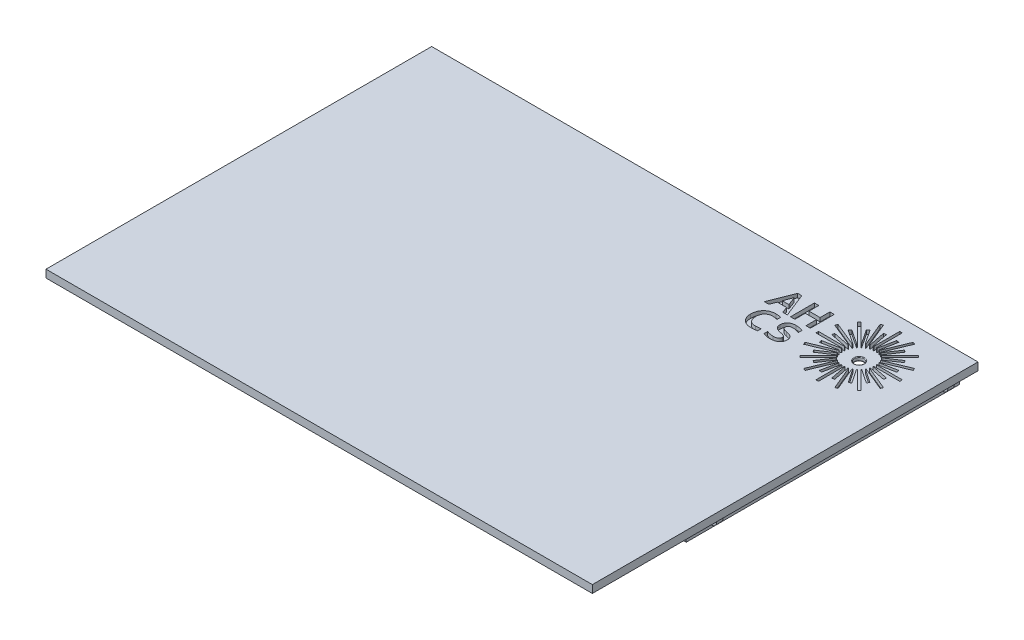
SolidWorks part; units mm, degrees
ref_plane "Front Plane" through (0, 0, 0) normal (0, 0, 1) x (1, 0, 0)
ref_plane "Top Plane" through (0, 0, 0) normal (0, 1, 0) x (1, 0, 0)
ref_plane "Right Plane" through (0, 0, 0) normal (1, 0, 0) x (0, 0, -1)
sketch "Sketch1" plane through (0, 0, 0) normal (0, 1, 0) x (1, 0, 0)
  line L1 (-107.95, -57.15) -> (107.95, -57.15)
  line L2 (-107.95, -57.15) -> (-107.95, 57.15)
  line L3 (-107.95, 57.15) -> (107.95, 57.15)
  line L4 (107.95, -57.15) -> (107.95, 57.15)
  line L5 (-107.95, -57.15) -> (107.95, 57.15) construction
  line L6 (-107.95, 57.15) -> (107.95, -57.15) construction
  point P0 (0, 0)
  dimension "D1" = 215.9
  dimension "D2" = 114.3
extrude "Boss-Extrude1" add sketch "Sketch1" along normal blind 3.048
sketch "Sketch5" plane through (0, 0, -57.15) normal (0, 0, -1) x (-1, 0, 0)
  line L1 (-107.95, 3.048) -> (107.95, 3.048)
  line L2 (-107.95, 3.048) -> (-107.95, 0)
  line L3 (-107.95, 0) -> (107.95, 0)
  line L4 (107.95, 3.048) -> (107.95, 0)
extrude "Boss-Extrude3" add sketch "Sketch5" along normal blind 38.1
sketch "Sketch6" plane through (0, 3.048, 0) normal (0, 1, 0) x (1, 0, 0)
  line L0 (-107.95, 95.25) -> (107.95, 95.25) construction
  line L1 (-107.95, 95.25) -> (-107.95, -57.15) construction
  circle A0 centre (82.55, 73.66) radius 6.35
  point P7 (82.55, 73.66)
  dimension "D1" = 12.7
  dimension "D2" = 21.59
  dimension "D3" = 190.5
extrude "Cut-Extrude1" cut sketch "Sketch6" against normal blind 1.524
sketch "Sketch7" plane through (0, 3.048, 0) normal (0, 1, 0) x (1, 0, 0)
  line L1 (82.042, 69.7818) -> (83.058, 69.7818)
  line L2 (82.042, 69.7818) -> (82.042, 90.2382)
  line L3 (82.042, 90.2382) -> (83.058, 90.2382)
  line L4 (83.058, 69.7818) -> (83.058, 90.2382)
  line L5 (82.042, 69.7818) -> (83.058, 90.2382) construction
  line L6 (82.042, 90.2382) -> (83.058, 69.7818) construction
  circle A0 centre (82.55, 73.66) radius 6.35 construction
  point P0 (82.55, 80.01)
extrude "Cut-Extrude2" cut sketch "Sketch7" against normal blind 1.524
pattern_circular "CirPattern1" count 16 over 360 about axis through (82.55, 0, -73.66) along (0, 1, 0) of "Cut-Extrude2"
sketch "Sketch8" plane through (0, 3.048, 0) normal (0, 1, 0) x (1, 0, 0)
  line L5 (82.55, 73.66) -> (84.4855, 83.3904) construction
  line L8 (82.55, 73.66) -> (-25.1585, 73.66) construction
  line L9 (79.5004, 60.9988) -> (84.5778, 86.5244)
  line L10 (79.5004, 60.9988) -> (80.5222, 60.7956)
  line L11 (84.5778, 86.5244) -> (85.5996, 86.3212)
  line L12 (80.5222, 60.7956) -> (85.5996, 86.3212)
  line L13 (79.5004, 60.9988) -> (85.5996, 86.3212) construction
  line L14 (84.5778, 86.5244) -> (80.5222, 60.7956) construction
  dimension "D1" = 101.25
extrude "Cut-Extrude4" cut sketch "Sketch8" against normal blind 1.524
pattern_circular "CirPattern2" count 16 over 360 about axis through (82.55, 0, -73.66) along (0, 1, 0) of "Cut-Extrude4"
sketch "Sketch9" plane through (0, 3.048, 0) normal (0, 1, 0) x (1, 0, 0)
  line L0 (19.05, 73.66) -> (89.5746, 73.66) construction
  line L2 (-107.95, 95.25) -> (107.95, 95.25) construction
  line L3 (44.45, 62.23) -> (64.77, 62.23) construction
  line L6 (-107.95, 95.25) -> (-107.95, -57.15) construction
  text T0 "<b>AH</b>" font "Corbel" height in points 36
  text T1 "<b>CS</b>" font "Corbel" height in points 36
  dimension "D1" = 152.4
  dimension "D2" = 21.59
  dimension "D3" = 11.43
extrude "Cut-Extrude5" cut sketch "Sketch9" against normal blind 1.524
sketch "Sketch10" plane through (0, 0, 0) normal (0, -1, 0) x (1, 0, 0)
  line L0 (107.95, 57.15) -> (107.95, -95.25) construction
  line L1 (103.886, -88.138) -> (100.33, -88.138)
  line L2 (103.886, -88.138) -> (103.886, 16.002)
  line L3 (103.886, 16.002) -> (100.33, 16.002)
  line L4 (100.33, -88.138) -> (100.33, 16.002)
  line L5 (103.886, -88.138) -> (100.33, 16.002) construction
  line L6 (103.886, 16.002) -> (100.33, -88.138) construction
  line L7 (107.95, -95.25) -> (-107.95, -95.25) construction
  point P0 (102.108, -36.068)
  dimension "D1" = 4.064
  dimension "D2" = 7.112
  dimension "D3" = 104.14
  dimension "D4" = 3.556
extrude "Boss-Extrude4" add sketch "Sketch10" along normal blind 5.08
sketch "Sketch11" plane through (0, 0, -88.138) normal (0, 0, -1) x (-1, 0, 0)
  line L0 (-103.886, -0.762) -> (-103.886, -4.318)
  line L4 (-103.886, -5.08) -> (-103.886, 0) construction
  line L5 (-107.95, 0) -> (107.95, 0) construction
  arc A3 (-103.886, -0.762) -> (-103.886, -4.318) centre (-103.886, -2.54) ccw
  dimension "D1" = 3.556
  dimension "D2" = 2.54
extrude "Boss-Extrude5" add sketch "Sketch11" against normal blind 2.54
sketch "Sketch12" plane through (0, 0, -88.138) normal (0, 0, -1) x (-1, 0, 0)
  line L1 (-103.886, 0) -> (-100.33, 0)
  line L2 (-103.886, 0) -> (-103.886, -5.08)
  line L3 (-103.886, -5.08) -> (-100.33, -5.08)
  line L4 (-100.33, 0) -> (-100.33, -5.08)
extrude "Boss-Extrude6" add sketch "Sketch12" along normal blind 3.81
pattern_linear "LPattern1" count 2 spacing 91.44 along (0, 0, 1) of "Boss-Extrude5"
ref_plane "Plane10" through (0, 0, -88.138) normal (0, 0, -1) x (-1, 0, 0)
mirror "Mirror1" about plane through (0, 0, 0) normal (1, 0, 0) of "Boss-Extrude4", "Boss-Extrude5", "LPattern1", "Boss-Extrude6"
sketch "Sketch16" plane through (100.33, 0, 0) normal (-1, 0, 0) x (0, 0, 1)
  line L0 (-91.948, -5.08) -> (16.002, -5.08) construction
  line L1 (-91.948, 0) -> (-89.154, 0)
  line L2 (-91.948, 0) -> (-91.948, -5.08)
  line L3 (-91.948, -5.08) -> (-89.154, -5.08)
  line L4 (-89.154, 0) -> (-89.154, -5.08)
  dimension "D1" = 2.794
extrude "Boss-Extrude7" add sketch "Sketch16" along normal blind 203.2
sketch "Sketch17" plane through (100.33, 0, 0) normal (-1, 0, 0) x (0, 0, 1)
  line L1 (-91.948, -5.08) -> (16.002, -5.08) construction
  line L2 (16.002, 0) -> (13.208, 0)
  line L3 (16.002, 0) -> (16.002, -5.08)
  line L4 (16.002, -5.08) -> (13.208, -5.08)
  line L5 (13.208, 0) -> (13.208, -5.08)
  dimension "D1" = 2.794
extrude "Boss-Extrude8" add sketch "Sketch17" along normal blind 203.2
sketch "Sketch19" plane through (0, 3.048, 0) normal (0, 1, 0) x (1, 0, 0)
  line L0 (65.9718, 73.66) -> (99.1282, 73.66) construction
  line L1 (65.9718, 74.168) -> (65.9718, 73.152) construction
  line L2 (99.1282, 73.152) -> (99.1282, 74.168) construction
  line L3 (82.55, 90.2382) -> (82.55, 57.0818) construction
  line L4 (83.058, 90.2382) -> (82.042, 90.2382) construction
  line L5 (82.042, 57.0818) -> (83.058, 57.0818) construction
  circle A0 centre (82.55, 73.66) radius 1.9
  dimension "D1" = 3.8
  dimension "D2" = 3.8
extrude "Cut-Extrude6" cut sketch "Sketch19" against normal blind 203.2
fillet "Fillet1" radius 0.254 1 edges at (82.55, 1.524, -71.76)
fillet "Fillet2" radius 0.254 1 edges at (82.55, 0, -75.56)
